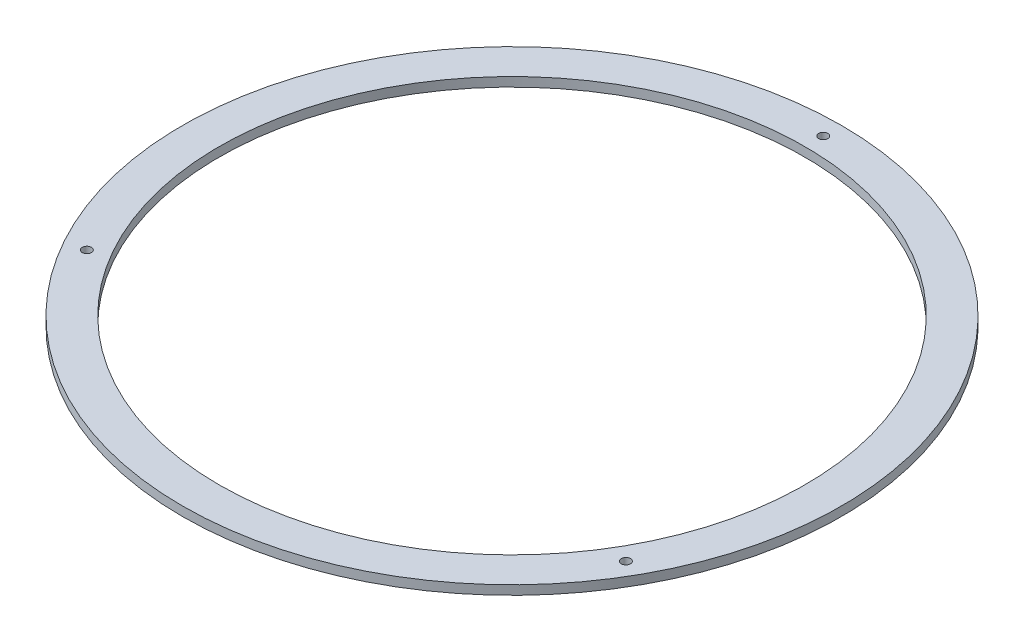
SolidWorks part; units mm, degrees
ref_plane "Front Plane" through (0, 0, 0) normal (0, 0, 1) x (1, 0, 0)
ref_plane "Top Plane" through (0, 0, 0) normal (0, 1, 0) x (1, 0, 0)
ref_plane "Right Plane" through (0, 0, 0) normal (1, 0, 0) x (0, 0, -1)
sketch "Sketch1" plane through (0, 0, 0) normal (0, 1, 0) x (1, 0, 0)
  circle A0 centre (0, 0) radius 228.6
  dimension "D1" = 457.2
extrude "Boss-Extrude1" add sketch "Sketch1" along normal blind 6.35 contours A0
sketch "Sketch2" plane through (0, 6.35, 0) normal (0, 1, 0) x (1, 0, 0)
  line L1 (0, 215.9) -> (-186.9749, -107.95) construction
  line L2 (-186.9749, -107.95) -> (186.9749, -107.95) construction
  line L3 (186.9749, -107.95) -> (0, 215.9) construction
  circle A0 centre (0, 215.9) radius 3.175
  circle A1 centre (0, 0) radius 228.6 construction
  circle A2 centre (0, 0) radius 107.95 construction
  circle A3 centre (-186.9749, -107.95) radius 3.175
  circle A4 centre (186.9749, -107.95) radius 3.175
  dimension "D1" = 6.35
  dimension "D2" = 215.9
  dimension "D3" = 6.35
  dimension "D4" = 6.35
extrude "Cut-Extrude1" cut sketch "Sketch2" against normal through all both and the other way through all
sketch "Sketch3" plane through (0, 6.35, 0) normal (0, 1, 0) x (1, 0, 0)
  circle A0 centre (0, 0) radius 203.2
  dimension "D1" = 406.4
extrude "Cut-Extrude2" cut sketch "Sketch3" against normal through all both and the other way through all
